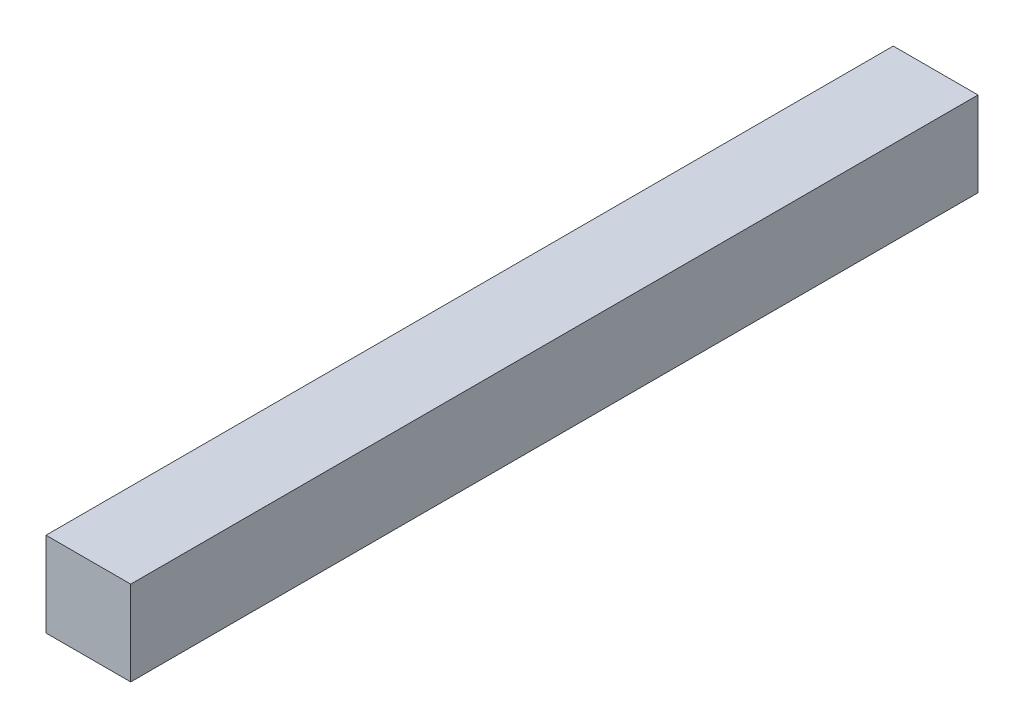
SolidWorks part; units mm, degrees
ref_plane "Front Plane" through (0, 0, 0) normal (0, 0, 1) x (1, 0, 0)
ref_plane "Top Plane" through (0, 0, 0) normal (0, 1, 0) x (1, 0, 0)
ref_plane "Right Plane" through (0, 0, 0) normal (1, 0, 0) x (0, 0, -1)
sketch "Sketch1" plane through (0, 0, 0) normal (0, 0, 1) x (1, 0, 0)
  line L1 (0, 0) -> (-1000, 0)
  line L2 (0, 0) -> (0, -1000)
  line L3 (0, -1000) -> (-1000, -1000)
  line L4 (-1000, 0) -> (-1000, -1000)
  dimension "D1" = 1000
extrude "Boss-Extrude1" add sketch "Sketch1" along normal blind 10000
